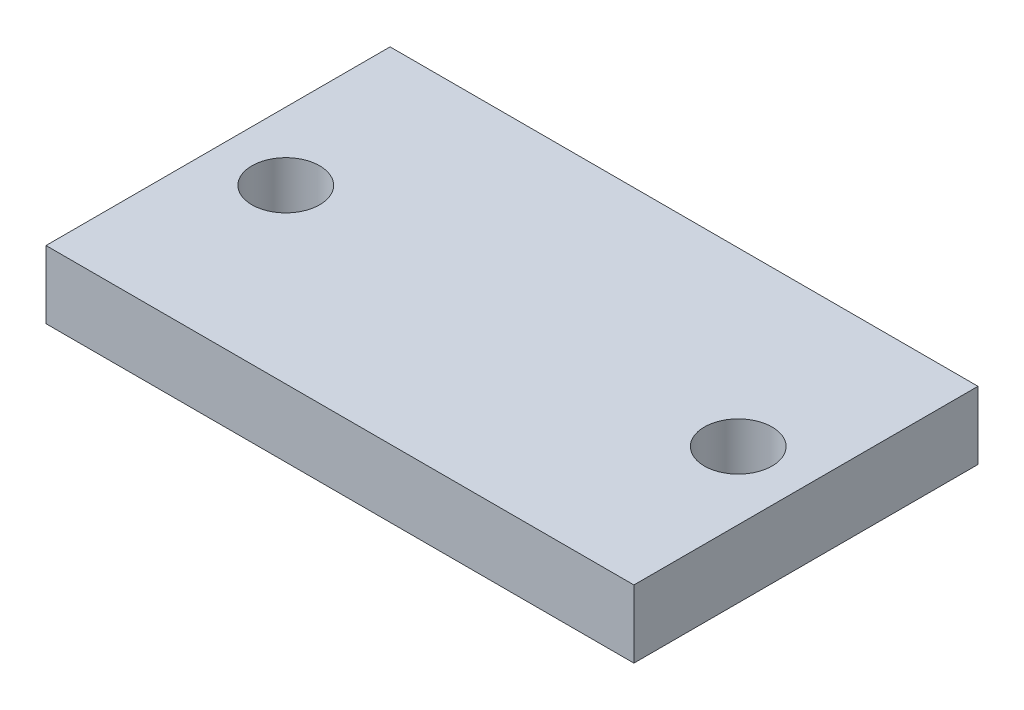
SolidWorks part; units mm, degrees
ref_plane "Front Plane" through (0, 0, 0) normal (0, 0, 1) x (1, 0, 0)
ref_plane "Top Plane" through (0, 0, 0) normal (0, 1, 0) x (1, 0, 0)
ref_plane "Right Plane" through (0, 0, 0) normal (1, 0, 0) x (0, 0, -1)
sketch "Sketch2" plane through (0, 0, 0) normal (0, 1, 0) x (1, 0, 0)
  line L0 (0, 25.4) -> (10.2, 35.6)
  line L1 (0, 0) -> (25.4, 0)
  line L2 (0, 0) -> (0, 25.4)
  line L3 (0, 25.4) -> (25.4, 25.4)
  line L4 (25.4, 0) -> (25.4, 25.4)
  line L5 (25.4, 25.4) -> (15.2, 35.6)
  line L6 (10.2, 35.6) -> (15.2, 35.6)
  line L7 (35.6, 15.2) -> (35.6, 10.2)
  line L8 (25.4, 25.4) -> (35.6, 15.2)
  line L9 (25.4, 0) -> (35.6, 10.2)
  line L10 (15.2, -10.2) -> (10.2, -10.2)
  line L11 (25.4, 0) -> (15.2, -10.2)
  line L12 (0, 0) -> (10.2, -10.2)
  line L13 (-10.2, 10.2) -> (-10.2, 15.2)
  line L14 (0, 0) -> (-10.2, 10.2)
  line L15 (0, 25.4) -> (-10.2, 15.2)
  point P5 (12.7, 12.7)
  point P23 (12.7, 12.7)
  dimension "D1" = 25.4
  dimension "D2" = 25.4
  dimension "D3" = 45
  dimension "D4" = 5
  dimension "D5" = 45
  dimension "D6" = 4
extrude "Boss-Extrude6" add sketch "Sketch2" along normal blind 5 contours L1 L4 L3 L2
sketch "Sketch4" plane through (0, 0, 0) normal (0, -1, 0) x (1, 0, 0)
  line L0 (25.4, 0) -> (25.4, -25.4) construction
  line L1 (25.4, 0) -> (25.4, -9.7)
  line L2 (25.4, -15.7) -> (25.4, -25.4)
  line L3 (25.4, -25.4) -> (15.7, -25.4)
  line L4 (9.7, -25.4) -> (0, -25.4)
  line L5 (0, -25.4) -> (0, -15.7)
  line L6 (0, -9.7) -> (0, 0)
  line L7 (0, 0) -> (9.7, 0)
  line L8 (15.7, 0) -> (25.4, 0)
  line L9 (9.7, 0) -> (15.7, 0)
  arc A0 (25.4, -15.7) -> (25.4, -9.7) centre (29.4, -12.7) ccw
  arc A1 (9.7, -25.4) -> (15.7, -25.4) centre (12.7, -29.4) ccw
  arc A2 (0, -9.7) -> (0, -15.7) centre (-4, -12.7) ccw
  arc A4 (15.7, 0) -> (9.7, 0) centre (12.7, 4) ccw [skipped]
  point P1 (12.7, -12.7)
  point P28 (12.7, -12.7)
  dimension "D1" = 10
  dimension "D2" = 4
  dimension "D3" = 4
extrude "Boss-Extrude7" add sketch "Sketch4" against normal blind 5
fillet "Fillet1" radius 5 6 edges at (25.4, 2.5, -15.7) (25.4, 2.5, -9.7) (0, 2.5, -9.7) (0, 2.5, -15.7) (9.7, 2.5, -25.4) (15.7, 2.5, -25.4)
sketch "Sketch5" plane through (0, 5, 0) normal (0, 1, 0) x (1, 0, 0)
  circle A0 centre (-4, 12.7) radius 1
  circle A1 centre (12.7, 29.4) radius 1
  circle A2 centre (29.4, 12.7) radius 1
  circle A3 centre (12.7, -4) radius 1 [skipped]
  point P3 (12.7, 12.7)
  point P13 (12.7, 12.7)
  dimension "D1" = 2
  dimension "D2" = 4
extrude "Cut-Extrude1" cut sketch "Sketch5" against normal blind 5
sketch "Sketch6" plane through (0, 5, 0) normal (0, 1, 0) x (1, 0, 0)
  line L1 (0, 25.4) -> (28.0983, 25.4)
  line L2 (0, 25.4) -> (0, 35.2018)
  line L3 (0, 35.2018) -> (28.0983, 35.2018)
  line L4 (28.0983, 25.4) -> (28.0983, 35.2018)
extrude "Cut-Extrude2" cut sketch "Sketch6" against normal through all
sketch "Sketch7" plane through (0, 5, 0) normal (0, 1, 0) x (1, 0, 0)
  line L1 (-9, 25.4) -> (34.4, 25.4)
  line L2 (-9, 25.4) -> (-9, 0)
  line L3 (-9, 0) -> (34.4, 0)
  line L4 (34.4, 25.4) -> (34.4, 0)
  arc A0 (-4.5, 17.6749) -> (-4.5, 7.7251) centre (-4, 12.7) ccw construction
  arc A1 (29.9, 7.7251) -> (29.9, 17.6749) centre (29.4, 12.7) ccw construction
  circle A2 centre (-4, 12.7) radius 2.5
  circle A3 centre (29.4, 12.7) radius 2.5
  dimension "D1" = 5
  dimension "D2" = 5
extrude "Boss-Extrude8" add sketch "Sketch7" against normal up to surface (5 mm away) up to face at (-4, 0, -11.7)
sketch "Sketch8" plane through (0, 5, 0) normal (0, 1, 0) x (1, 0, 0)
  circle A0 centre (-4, 12.7) radius 2.5
  circle A1 centre (29.4, 12.7) radius 2.5
  dimension "D1" = 5
  dimension "D2" = 5
extrude "Cut-Extrude3" cut sketch "Sketch8" against normal blind 10
